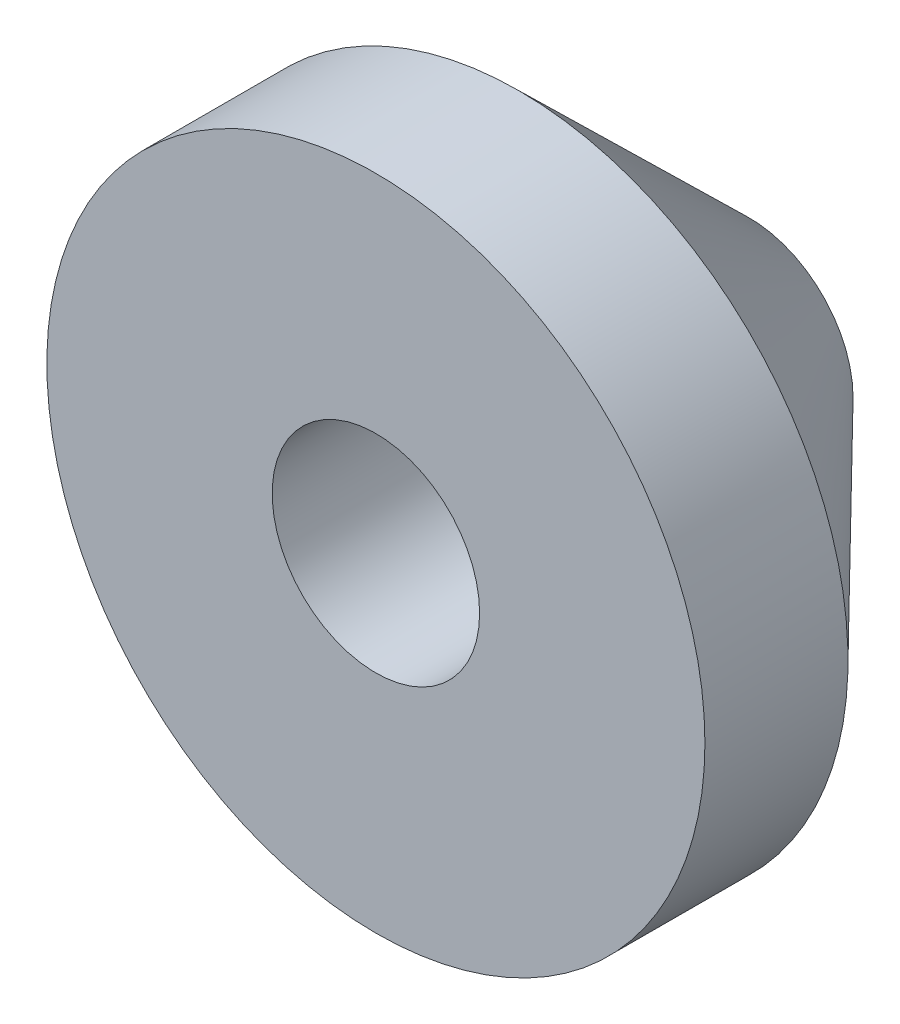
SolidWorks part; units mm, degrees
ref_plane "Plan de face" through (0, 0, 0) normal (0, 0, 1) x (1, 0, 0)
ref_plane "Plan de dessus" through (0, 0, 0) normal (0, 1, 0) x (1, 0, 0)
ref_plane "Plan de droite" through (0, 0, 0) normal (1, 0, 0) x (0, 0, -1)
sketch "Esquisse1" plane through (0, 0, 0) normal (0, 0, 1) x (1, 0, 0)
  circle A0 centre (0, 0) radius 11.5
extrude "Boss.-Extru.1" add sketch "Esquisse1" along normal blind 5
sketch "Esquisse4" plane through (0, 0, 0) normal (1, 0, 0) x (0, 0, -1)
  line L0 (0, 11.5) -> (0, 0)
  line L1 (0, -11.5) -> (0, 11.5) construction
  line L2 (0, 11.5) -> (7.1569, 4.5)
  line L5 (7.1569, 4.5) -> (11.7578, 0)
  line L6 (0, 0) -> (11.7578, 0)
  point P7 (0, 4.5)
  point P9 (0, 0.3621)
revolve "Révolution1" add sketch "Esquisse4" angle 360 about L6
sketch "Esquisse6" plane through (0, 0, 5) normal (0, 0, 1) x (1, 0, 0)
  circle A0 centre (0, 0) radius 3.625
extrude "Enlèv. mat.-Extru.1" cut sketch "Esquisse6" against normal through all
